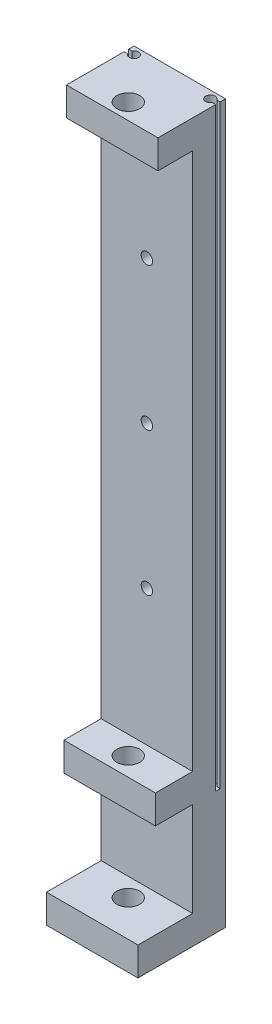
SolidWorks part; units mm, degrees
ref_plane "Front Plane" through (0, 0, 0) normal (0, 0, 1) x (1, 0, 0)
ref_plane "Top Plane" through (0, 0, 0) normal (0, 1, 0) x (1, 0, 0)
ref_plane "Right Plane" through (0, 0, 0) normal (1, 0, 0) x (0, 0, -1)
sketch "Sketch1" plane through (0, 0, 0) normal (0, 1, 0) x (1, 0, 0)
  line L1 (-16, -15.3) -> (16, -15.3)
  line L2 (-16, -15.3) -> (-16, 15.3)
  line L3 (-16, 15.3) -> (16, 15.3)
  line L4 (16, -15.3) -> (16, 15.3)
  line L5 (-16, -15.3) -> (16, 15.3) construction
  line L6 (-16, 15.3) -> (16, -15.3) construction
  point P0 (0, 0)
  dimension "D1" = 30.6
  dimension "D2" = 32
extrude "Boss-Extrude1" add sketch "Sketch1" along normal blind 10
ref_plane "Plane1" through (0, 251, 0) normal (0, -1, 0) x (-1, 0, 0)
sketch "Sketch2" plane through (0, 10, 0) normal (0, 1, 0) x (1, 0, 0)
  line L0 (16, 15.3) -> (-16, 15.3) construction
  line L1 (-16, 15.3) -> (16, 15.3)
  line L2 (-16, 15.3) -> (-16, 3.8)
  line L3 (-16, 3.8) -> (16, 3.8)
  line L4 (16, 15.3) -> (16, 3.8)
  line L5 (16, -15.3) -> (16, 15.3) construction
  dimension "D1" = 11.5
sketch "Sketch3" plane through (0, 251, 0) normal (0, -1, 0) x (-1, 0, 0)
  line L0 (-16, -15.3) -> (-16, 15.3) construction
  line L1 (16, 15.3) -> (-16, 15.3)
  line L2 (16, 15.3) -> (16, -8.3)
  line L3 (16, -8.3) -> (-16, -8.3)
  line L4 (-16, 15.3) -> (-16, -8.3)
  dimension "D1" = 23.6
extrude "Boss-Extrude2" add sketch "Sketch3" along normal blind 10 separate body
extrude "Boss-Extrude3" add sketch "Sketch2" along normal up to surface (231 mm away) up to face at (0, 241, -3.5)
ref_plane "Plane2" through (0, 53, 0) normal (0, -1, 0) x (-1, 0, 0)
sketch "Sketch4" plane through (0, 53, 0) normal (0, -1, 0) x (-1, 0, 0)
  line L0 (16, 15.3) -> (16, -15.3) construction
  line L1 (16, -9.2) -> (-16, -9.2)
  line L2 (16, -9.2) -> (16, 3.8)
  line L3 (16, 3.8) -> (-16, 3.8)
  line L4 (-16, -9.2) -> (-16, 3.8)
  line L5 (-16, -15.3) -> (-16, 15.3) construction
  line L6 (16, 3.8) -> (-16, 3.8) construction
  dimension "D1" = 13
extrude "Boss-Extrude4" add sketch "Sketch4" along normal blind 10
sketch "Sketch5" plane through (0, 43, 0) normal (0, -1, 0) x (1, 0, 0)
  line L0 (16, -3.8) -> (16, 9.2) construction
  circle A0 centre (0, 2.7) radius 4
  point P6 (16, 2.7)
  dimension "D1" = 8
extrude "Cut-Extrude1" cut sketch "Sketch5" against normal through all both and the other way through all
sketch "Sketch6" plane through (0, 0, -15.3) normal (0, 0, -1) x (-1, 0, 0)
  line L0 (0, 0) -> (0, 251) construction
  line L1 (16, 251) -> (-16, 251) construction
  line L2 (0, 50.5) -> (0, 100.5) construction
  line L3 (-16, 0) -> (16, 0) construction
  circle A0 centre (0, 50.5) radius 2
  circle A1 centre (0, 100.5) radius 2
  circle A2 centre (0, 150.5) radius 2
  circle A3 centre (0, 200.5) radius 2
  dimension "D1" = 4
  dimension "D2" = 50.5
  dimension "D4" = 50
  dimension "D3" = 4
extrude "Cut-Extrude2" cut sketch "Sketch6" against normal up to surface (11.5 mm away) up to face at (0, 147, -3.8)
sketch "Sketch7" plane through (0, 251, 0) normal (0, 1, 0) x (1, 0, 0)
  line L0 (-16, 11.85) -> (-16, 13.45)
  line L1 (-15, 3.764) -> (-15, 14.3) construction
  line L2 (-16, -8.3) -> (-16, 15.3) construction
  line L3 (-15, 14.3) -> (-5.3239, 14.3) construction
  line L4 (-16, 15.3) -> (16, 15.3) construction
  line L5 (0, 0) -> (0, 30.2216) construction
  line L6 (-14.7931, 11.85) -> (-16, 11.85)
  line L7 (-14.7931, 13.45) -> (-16, 13.45)
  line L8 (-13.35, 12.65) -> (-21.3611, 12.65) construction
  line L9 (14.7931, 13.45) -> (16, 13.45)
  line L10 (14.7931, 11.85) -> (16, 11.85)
  line L11 (16, 11.85) -> (16, 13.45)
  arc A0 (-14.7931, 11.85) -> (-14.7931, 13.45) centre (-13.35, 12.65) ccw
  arc A1 (14.7931, 11.85) -> (14.7931, 13.45) centre (13.35, 12.65) cw
  dimension "D1" = 3.3
  dimension "D2" = 1
  dimension "D3" = 1
  dimension "D4" = 1.6
extrude "Cut-Extrude3" cut sketch "Sketch7" against normal up to surface (208 mm away) up to face at (0, 43, -1.3)
equation "\"TotalLength\"= 251mm"
equation "\"D1@Plane1\"=\"TotalLength\""
equation "\"N\"= 4"
equation "\"D2@Sketch6\"=(\"TotalLength\"-(\"N\"-1)*50) /2"
